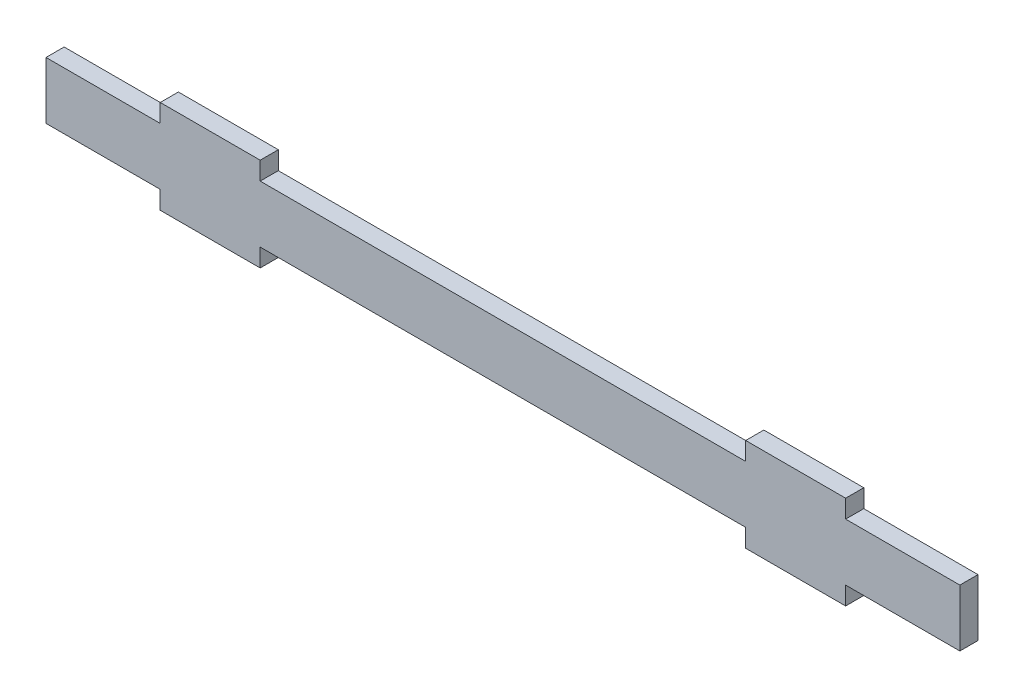
SolidWorks part; units mm, degrees
ref_plane "Front Plane" through (0, 0, 0) normal (0, 0, 1) x (1, 0, 0)
ref_plane "Top Plane" through (0, 0, 0) normal (0, 1, 0) x (1, 0, 0)
ref_plane "Right Plane" through (0, 0, 0) normal (1, 0, 0) x (0, 0, -1)
sketch "Sketch1" plane through (0, 0, 0) normal (0, 0, 1) x (1, 0, 0)
  line L0 (0, -5) -> (0, 2.9772) construction
  line L1 (-160, -5) -> (-120, -5)
  line L2 (-160, -5) -> (-160, 15)
  line L4 (160, -5) -> (160, 15)
  line L5 (-160, -5) -> (160, 5) construction
  line L6 (-160, 5) -> (160, -5) construction
  line L7 (-160, 5) -> (160, 5) construction
  line L8 (-85, -5) -> (-85, -11.35)
  line L9 (-85, -11.35) -> (-120, -11.35)
  line L10 (-120, -11.35) -> (-120, -5)
  line L11 (-85, -5) -> (85, -5)
  line L12 (85, -5) -> (85, -11.35)
  line L13 (85, -11.35) -> (120, -11.35)
  line L14 (120, -11.35) -> (120, -5)
  line L15 (120, -5) -> (160, -5)
  line L16 (-160, 5) -> (160, 15) construction
  line L17 (-160, 15) -> (160, 5) construction
  line L18 (0, 15) -> (0, 7.0228) construction
  line L19 (120, 15) -> (160, 15)
  line L20 (120, 21.35) -> (120, 15)
  line L21 (85, 21.35) -> (120, 21.35)
  line L22 (85, 15) -> (85, 21.35)
  line L23 (-85, 15) -> (85, 15)
  line L24 (-120, 21.35) -> (-120, 15)
  line L25 (-85, 21.35) -> (-120, 21.35)
  line L26 (-85, 15) -> (-85, 21.35)
  line L27 (-160, 15) -> (-120, 15)
  point P0 (0, 0)
  point P28 (0, 10)
  dimension "D1" = 10
  dimension "D2" = 320
  dimension "D3" = 6.35
  dimension "D4" = 35
  dimension "D5" = 120
extrude "Boss-Extrude1" add sketch "Sketch1" along normal blind 6.35
